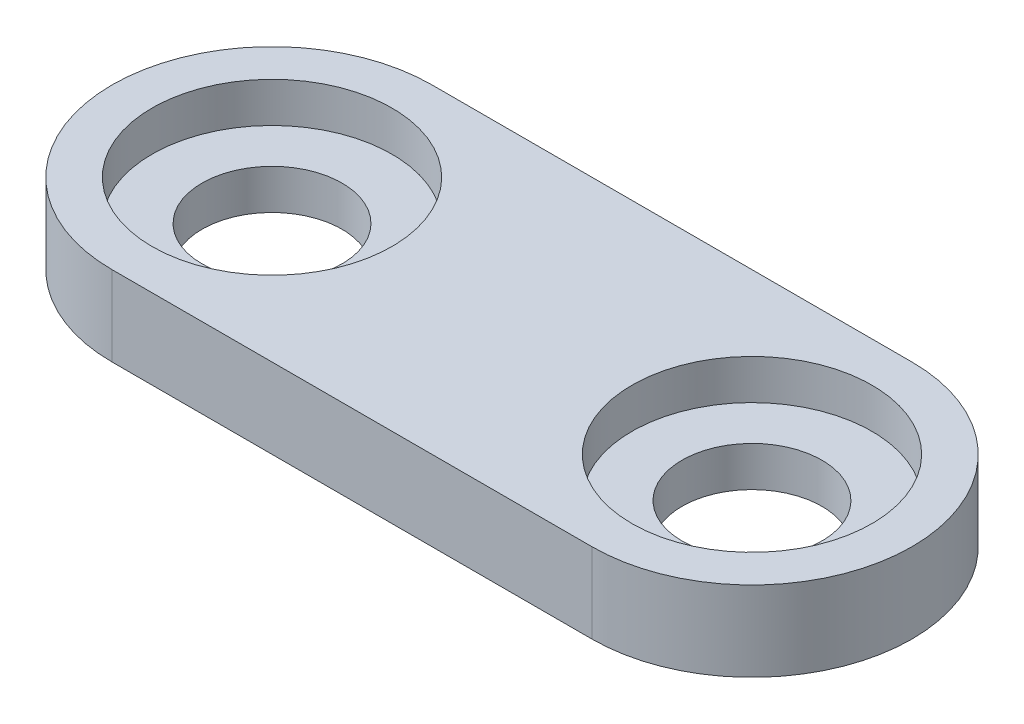
SolidWorks part; units mm, degrees
ref_plane "Front Plane" through (0, 0, 0) normal (0, 0, 1) x (1, 0, 0)
ref_plane "Top Plane" through (0, 0, 0) normal (0, 1, 0) x (1, 0, 0)
ref_plane "Right Plane" through (0, 0, 0) normal (1, 0, 0) x (0, 0, -1)
sketch "Sketch1" plane through (0, 0, 0) normal (0, 1, 0) x (1, 0, 0)
  line L0 (-6, 4) -> (6, 4)
  line L2 (6, -4) -> (-6, -4)
  arc A0 (6, -4) -> (6, 4) centre (6, 0) ccw
  arc A1 (-6, -4) -> (-6, 4) centre (-6, 0) cw
  circle A2 centre (-6, 0) radius 1.75
  circle A3 centre (6, 0) radius 1.75
  point P8 (0, -4)
  point P10 (0, 4)
  dimension "D2" = 3.5
  dimension "D3" = 3.5
  dimension "D1" = 8
  dimension "D4" = 12
extrude "Boss-Extrude1" add sketch "Sketch1" along normal blind 2
sketch "Sketch3" plane through (0, 2, 0) normal (0, 1, 0) x (1, 0, 0)
  circle A0 centre (-6, 0) radius 3
  circle A1 centre (6, 0) radius 3
  dimension "D1" = 6
  dimension "D2" = 6
extrude "Cut-Extrude1" cut sketch "Sketch3" against normal blind 1
